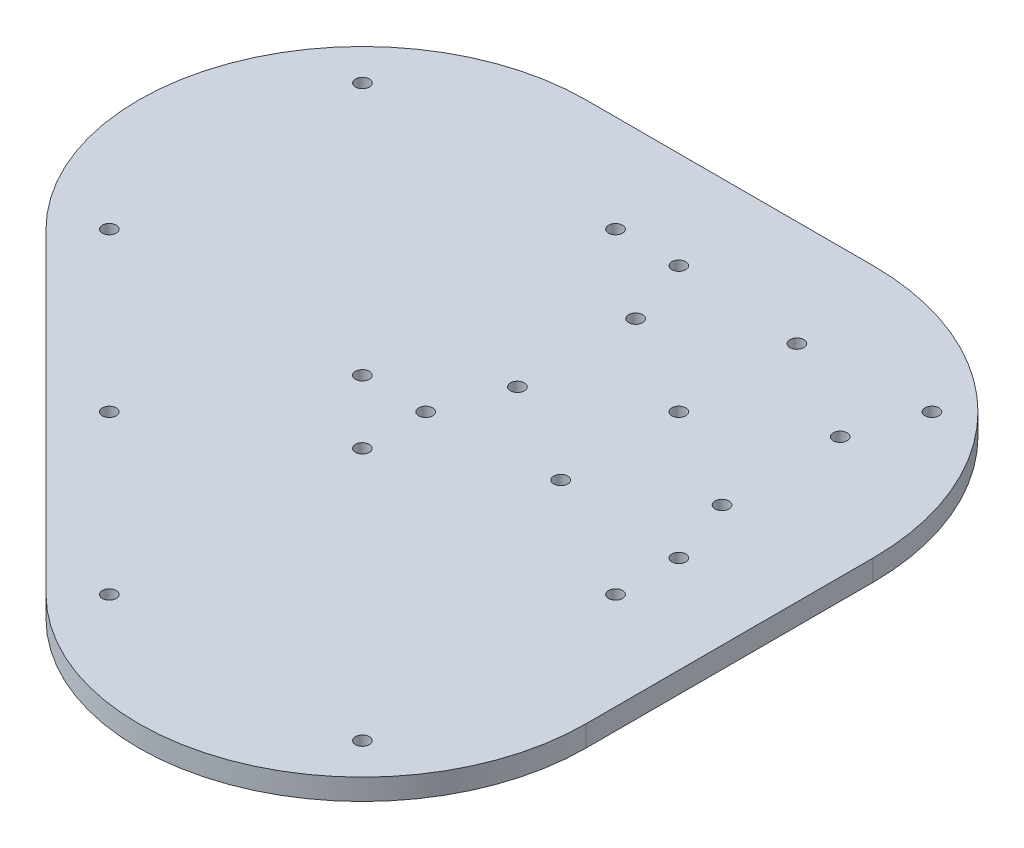
SolidWorks part; units mm, degrees
material "环氧树脂,未充填"
ref_plane "前视基准面" through (0, 0, 0) normal (0, 0, 1) x (1, 0, 0)
ref_plane "上视基准面" through (0, 0, 0) normal (0, 1, 0) x (1, 0, 0)
ref_plane "右视基准面" through (0, 0, 0) normal (1, 0, 0) x (0, 0, -1)
other "Configuration Table"
sketch "草图1" plane through (0, 0, 0) normal (0, 1, 0) x (1, 0, 0)
  line L0 (0, 75) -> (75, 0) construction
  line L5 (-129.2358, 37.5) -> (204.2358, 37.5) construction
  line L6 (37.5, -119.3963) -> (37.5, 194.3963) construction
  line L7 (-75, 0) -> (0, -75)
  line L9 (-152.0607, 0) -> (152.0607, 0) construction
  line L10 (0, -138.8093) -> (0, 138.8093) construction
  line L11 (90.533, -37.5) -> (90.533, 30.533)
  line L12 (-75, -75) -> (75, -75) construction
  line L13 (-75, -75) -> (-75, 75) construction
  line L14 (-75, 75) -> (75, 75) construction
  line L15 (75, -75) -> (75, 75) construction
  line L16 (-75, -75) -> (75, 75) construction
  line L17 (-75, 75) -> (75, -75) construction
  line L18 (-37.5, 90.533) -> (30.533, 90.533)
  line L19 (-37.5, -10.5569) -> (-37.5, 85.5569) construction
  line L22 (-37.0835, -37.5) -> (112.0835, -37.5) construction
  line L24 (-67.5, 7.5) -> (-7.5, 7.5) construction
  line L25 (-67.5, 7.5) -> (-67.5, 67.5) construction
  line L26 (-67.5, 67.5) -> (-7.5, 67.5) construction
  line L27 (-7.5, 7.5) -> (-7.5, 67.5) construction
  line L28 (-67.5, 7.5) -> (-7.5, 67.5) construction
  line L29 (-67.5, 67.5) -> (-7.5, 7.5) construction
  line L30 (-67.5, 7.5) -> (7.5, -67.5) construction
  circle A21 centre (37.5, 37.5) radius 28 construction
  circle A22 centre (37.5, 65.5) radius 1.65
  circle A23 centre (61.7487, 51.5) radius 1.65
  circle A24 centre (61.7487, 23.5) radius 1.65
  circle A25 centre (37.5, 9.5) radius 1.65
  circle A26 centre (13.2513, 23.5) radius 1.65
  circle A27 centre (13.2513, 51.5) radius 1.65
  arc A28 (0, -75) -> (75, -75) centre (37.5, -37.5) ccw
  arc A31 (75, -75) -> (90.533, -37.5) centre (37.5, -37.5) ccw
  arc A32 (90.533, 30.533) -> (30.533, 90.533) centre (30.533, 30.533) ccw
  arc A33 (-75, 0) -> (-75, 75) centre (-37.5, 37.5) cw
  arc A34 (-75, 75) -> (-37.5, 90.533) centre (-37.5, 37.5) cw
  circle A35 centre (7.5, 67.5) radius 1.65
  circle A36 centre (67.5, 67.5) radius 1.65
  circle A37 centre (67.5, 7.5) radius 1.65
  circle A38 centre (7.5, 7.5) radius 1.65
  circle A39 centre (37.5, 37.5) radius 1.65
  circle A40 centre (-67.5, 67.5) radius 1.65
  circle A41 centre (-7.5, 67.5) radius 1.65
  circle A42 centre (-67.5, 7.5) radius 1.65
  circle A43 centre (-7.5, 7.5) radius 1.65
  circle A44 centre (7.5, -67.5) radius 1.65
  circle A45 centre (7.5, -7.5) radius 1.65
  circle A46 centre (67.5, -7.5) radius 1.65
  circle A47 centre (67.5, -67.5) radius 1.65
  circle A48 centre (-30, -30) radius 1.65
  point P12 (37.5, 37.5)
  point P18 (37.5, 37.5)
  point P19 (37.5, 37.5)
  point P41 (-37.5, 37.5)
  point P44 (37.5, -37.5)
  point P52 (0, 0)
  point P55 (0, 0)
  point P58 (0, 0)
  point P65 (66.6742, 66.6742)
  point P75 (37.5, 37.5)
  point P78 (37.5, 37.5)
  dimension "D3" = 60
  dimension "D5" = 60
  dimension "D7" = 60
  dimension "D8" = 60
  dimension "D14" = 56
  dimension "D15" = 3.3
  dimension "D4" = 3.3
  dimension "D6" = 3.3
  dimension "D9" = 3.3
  dimension "D10" = 3.3
  dimension "D2" = 6
  dimension "D13" = 150
extrude "凸台-拉伸1" add sketch "草图1" along normal blind 5
